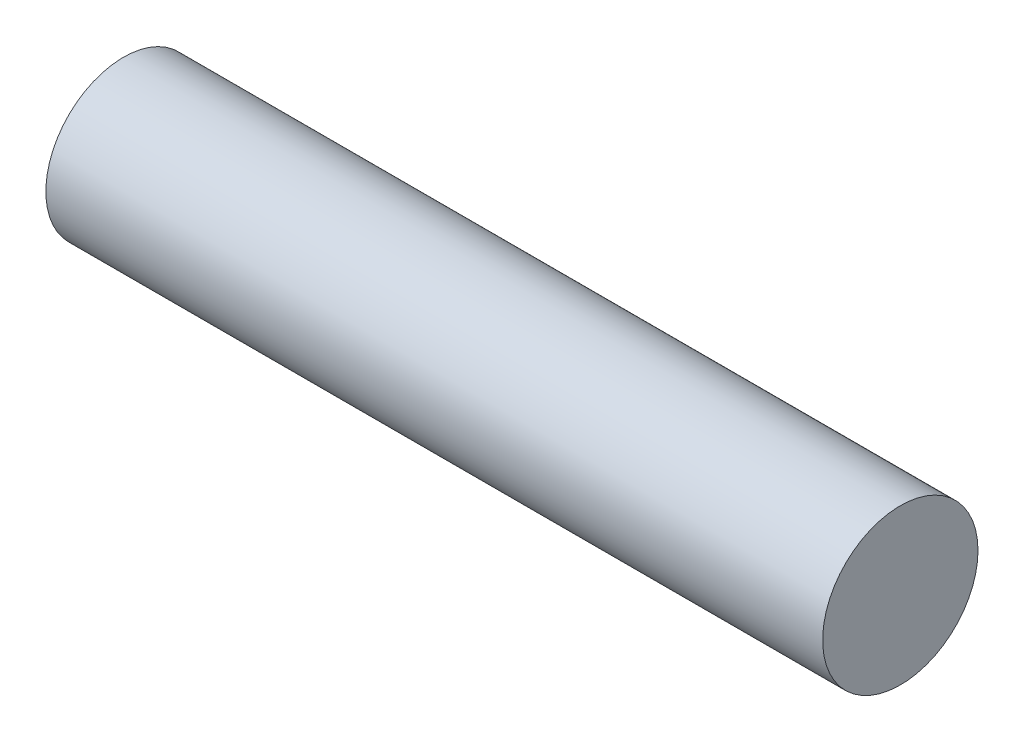
SolidWorks part; units mm, degrees
ref_plane "Front Plane" through (0, 0, 0) normal (0, 0, 1) x (1, 0, 0)
ref_plane "Top Plane" through (0, 0, 0) normal (0, 1, 0) x (1, 0, 0)
ref_plane "Right Plane" through (0, 0, 0) normal (1, 0, 0) x (0, 0, -1)
sketch "Sketch1" plane through (0, 0, 0) normal (1, 0, 0) x (0, 0, -1)
  circle A0 centre (0, 0) radius 5
  dimension "D1" = 10
extrude "Boss-Extrude1" add sketch "Sketch1" along normal mid plane 50
